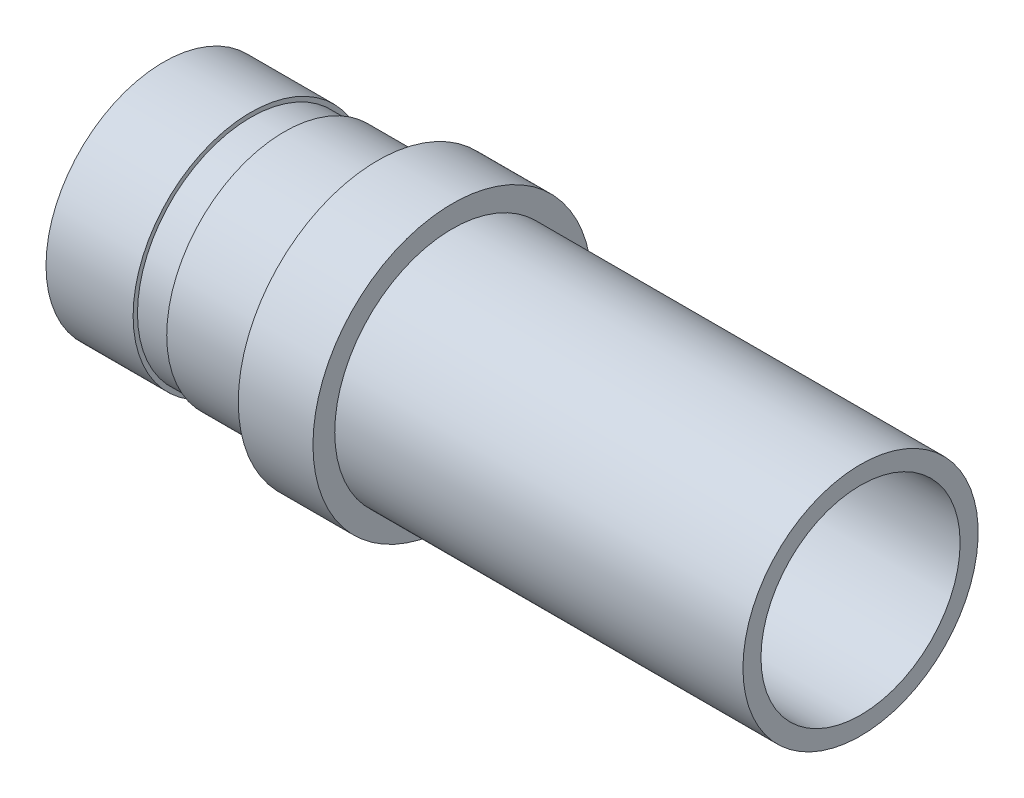
SolidWorks part; units mm, degrees
ref_plane "Plano frontal" through (0, 0, 0) normal (0, 0, 1) x (1, 0, 0)
ref_plane "Plano superior" through (0, 0, 0) normal (0, 1, 0) x (1, 0, 0)
ref_plane "Plano direito" through (0, 0, 0) normal (1, 0, 0) x (0, 0, -1)
sketch "Esboço1" plane through (0, 0, 0) normal (0, 0, 1) x (1, 0, 0)
  line L0 (0, 0) -> (28, 0) construction
  line L1 (0, 4.725) -> (3.5, 4.725)
  line L2 (3.5, 4.725) -> (3.5, 4.55)
  line L3 (3.5, 4.55) -> (4.85, 4.55)
  line L4 (4.85, 4.55) -> (4.85, 4.725)
  line L5 (4.85, 4.725) -> (8.6, 4.725)
  line L6 (8.6, 4.725) -> (8.6, 5.6)
  line L7 (8.6, 5.6) -> (11.6, 5.6)
  line L8 (11.6, 5.6) -> (11.6, 4.725)
  line L9 (11.6, 4.725) -> (28, 4.725)
  line L10 (28, 4.725) -> (28, 4)
  line L11 (0, 4.725) -> (0, 4)
  line L12 (0, 4) -> (28, 4)
  dimension "D1" = 9.45
  dimension "D2" = 11.2
  dimension "D3" = 9.45
  dimension "D4" = 9.1
  dimension "D5" = 9.45
  dimension "D6" = 3
  dimension "D7" = 1.35
  dimension "D8" = 28
  dimension "D9" = 3.5
  dimension "D10" = 3.75
  dimension "D11" = 8
revolve "Revolução1" add sketch "Esboço1" angle 360 about L0
